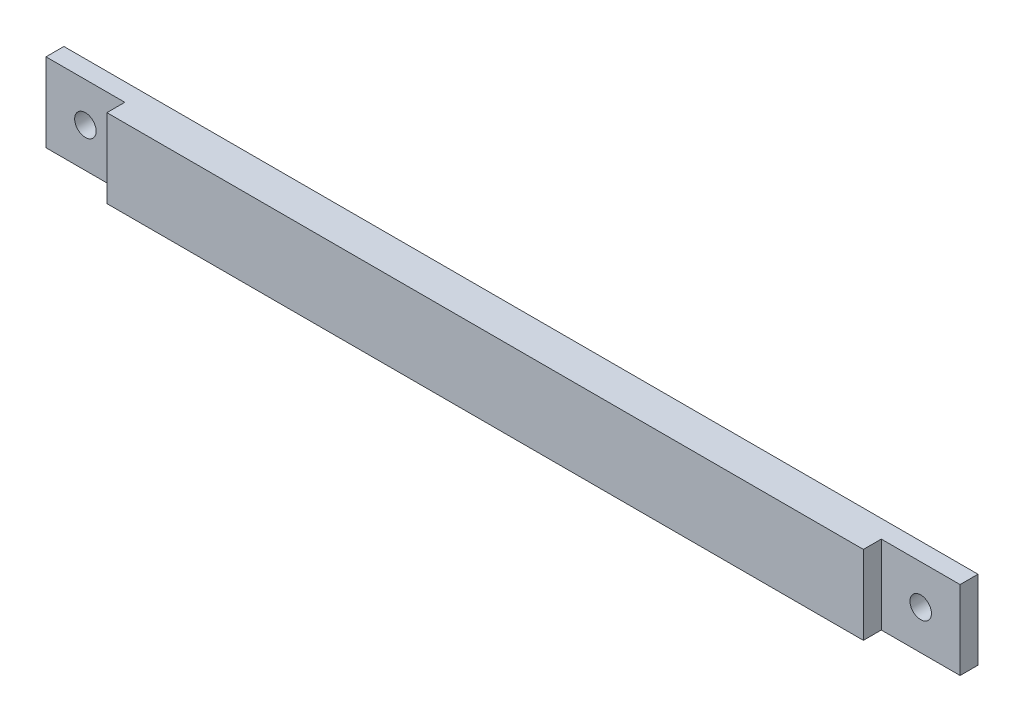
SolidWorks part; units mm, degrees
ref_plane "Plan de face" through (0, 0, 0) normal (0, 0, 1) x (1, 0, 0)
ref_plane "Plan de dessus" through (0, 0, 0) normal (0, 1, 0) x (1, 0, 0)
ref_plane "Plan de droite" through (0, 0, 0) normal (1, 0, 0) x (0, 0, -1)
sketch "Esquisse1" plane through (0, 0, 0) normal (0, 0, 1) x (1, 0, 0)
  line L1 (-102.5284, 45.8562) -> (152.6716, 45.8562)
  line L2 (-102.5284, 45.8562) -> (-102.5284, 23.8562)
  line L3 (-102.5284, 23.8562) -> (152.6716, 23.8562)
  line L4 (152.6716, 45.8562) -> (152.6716, 23.8562)
  circle A0 centre (-91.5284, 34.8562) radius 3
  circle A1 centre (141.6716, 34.8562) radius 3
  dimension "D3" = 6
  dimension "D4" = 11
  dimension "D5" = 11
  dimension "D6" = 6
  dimension "D7" = 11
  dimension "D1" = 255.2
  dimension "D2" = 22
extrude "Boss.-Extru.1" add sketch "Esquisse1" along normal blind 10
sketch "Esquisse2" plane through (0, 0, 10) normal (0, 0, 1) x (1, 0, 0)
  line L0 (-102.5284, 23.8562) -> (152.6716, 23.8562) construction
  line L1 (-102.5284, 45.8562) -> (-80.5284, 45.8562)
  line L2 (-102.5284, 45.8562) -> (-102.5284, 23.8562)
  line L3 (-102.5284, 23.8562) -> (-80.5284, 23.8562)
  line L4 (-80.5284, 45.8562) -> (-80.5284, 23.8562)
  line L6 (152.6716, 45.8562) -> (130.6716, 45.8562)
  line L7 (152.6716, 45.8562) -> (152.6716, 23.8562)
  line L8 (152.6716, 23.8562) -> (130.6716, 23.8562)
  line L9 (130.6716, 45.8562) -> (130.6716, 23.8562)
  dimension "D1" = 22
  dimension "D2" = 22
extrude "Enlèv. mat.-Extru.1" cut sketch "Esquisse2" against normal blind 5
